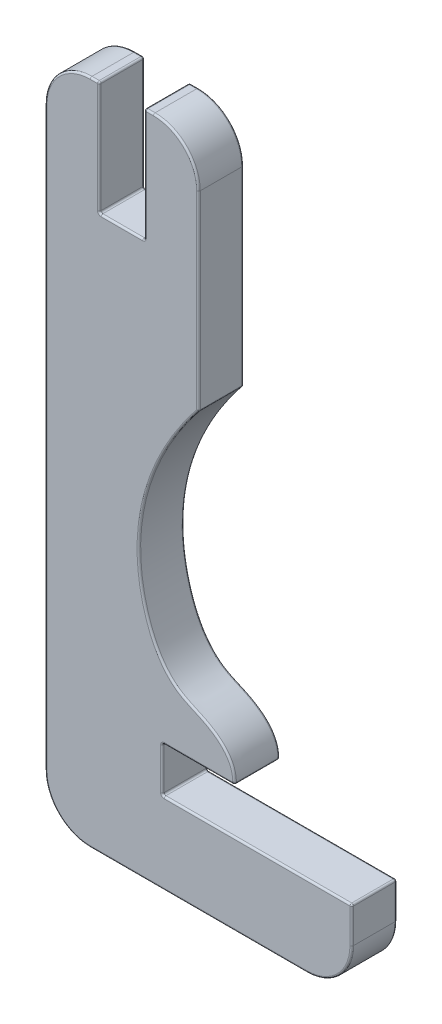
SolidWorks part; units mm, degrees
ref_plane "Plano frontal" through (0, 0, 0) normal (0, 0, 1) x (1, 0, 0)
ref_plane "Plano superior" through (0, 0, 0) normal (0, 1, 0) x (1, 0, 0)
ref_plane "Plano direito" through (0, 0, 0) normal (1, 0, 0) x (0, 0, -1)
sketch "Esboço1" plane through (0, 0, 0) normal (0, 0, 1) x (1, 0, 0)
  line L33 (-99.4597, 15.411) -> (-99.4597, 4.8613)
  line L106 (-105.4597, 17.911) -> (-104.9597, 17.911)
  line L107 (-107.9597, 15.411) -> (-107.9597, -16.589)
  line L108 (-105.4597, -19.089) -> (-93.4597, -19.089)
  line L109 (-90.9597, -14.589) -> (-90.9597, -16.589)
  line L110 (-90.9597, -14.589) -> (-101.4597, -14.589)
  line L112 (-104.9597, 17.911) -> (-104.9597, 11.611)
  line L113 (-104.9597, 11.611) -> (-102.4597, 11.611)
  line L114 (-102.4597, 17.911) -> (-102.4597, 11.611)
  line L115 (-101.4597, -14.589) -> (-101.4597, -12.089)
  line L116 (-101.4597, -12.089) -> (-97.4597, -12.089)
  line L117 (-102.4597, 17.911) -> (-101.9597, 17.911)
  arc A24 (-99.4597, 15.411) -> (-101.9597, 17.911) centre (-101.9597, 15.411) ccw
  arc A25 (-105.4597, 17.911) -> (-107.9597, 15.411) centre (-105.4597, 15.411) ccw
  arc A26 (-93.4597, -19.089) -> (-90.9597, -16.589) centre (-93.4597, -16.589) ccw
  arc A27 (-107.9597, -16.589) -> (-105.4597, -19.089) centre (-105.4597, -16.589) ccw
  spline S0 degree 3 poles (-97.4597, -12.089) (-97.4046, -10.9915) (-98.6583, -9.9048) (-101.3041, -8.9908) (-103.9158, -3.2315) (-101.9906, 1.7088) (-99.4597, 4.8613) knots 0 0 0 0 0.150349 0.226705 0.420402 1 1 1 1
  dimension "D1" = 6.3
  dimension "D65" = 2.5
  dimension "D66" = 2.5
  dimension "D59" = 2.5
  dimension "D60" = 3
  dimension "D61" = 4.5
  dimension "D62" = 10.5
  dimension "D63" = 2.5
  dimension "D64" = 4
extrude "Ressalto-extrusão1" add sketch "Esboço1" along normal blind 2.5
fillet "Filete1" radius 0.1 43 edges at (-102.4597, 17.911, 1.25) (-102.4597, 11.611, 1.25) (-104.9597, 11.611, 1.25) (-104.9597, 17.911, 1.25) (-90.9597, -14.589, 1.25) (-101.4597, -14.589, 1.25) (-101.4597, -12.089, 1.25) (-97.4597, -12.089, 1.25) (-99.4597, 4.8613, 1.25) (-99.4597, 10.1362, 2.5) (-99.4597, -12.089, 2.5) (-101.4597, -13.339, 2.5) (-96.2097, -14.589, 2.5) (-90.9597, -15.589, 2.5) (-91.6919, -18.3568, 2.5) (-99.4597, -19.089, 2.5) (-107.2275, -18.3568, 2.5) (-107.9597, -0.589, 2.5) (-107.2275, 17.1787, 2.5) (-105.2097, 17.911, 2.5) (-104.9597, 14.761, 2.5) (-103.7097, 11.611, 2.5) (-102.4597, 14.761, 2.5) (-102.2097, 17.911, 2.5) (-100.1919, 17.1787, 2.5) (-102.2097, 17.911, 0) (-102.4597, 14.761, 0) (-103.7097, 11.611, 0) (-104.9597, 14.761, 0) (-105.2097, 17.911, 0) (-107.2275, 17.1787, 0) (-107.9597, -0.589, 0) (-107.2275, -18.3568, 0) (-99.4597, -19.089, 0) (-91.6919, -18.3568, 0) (-90.9597, -15.589, 0) (-96.2097, -14.589, 0) (-101.4597, -13.339, 0) (-99.4597, -12.089, 0) (-99.4597, 10.1362, 0) (-100.1919, 17.1787, 0)
